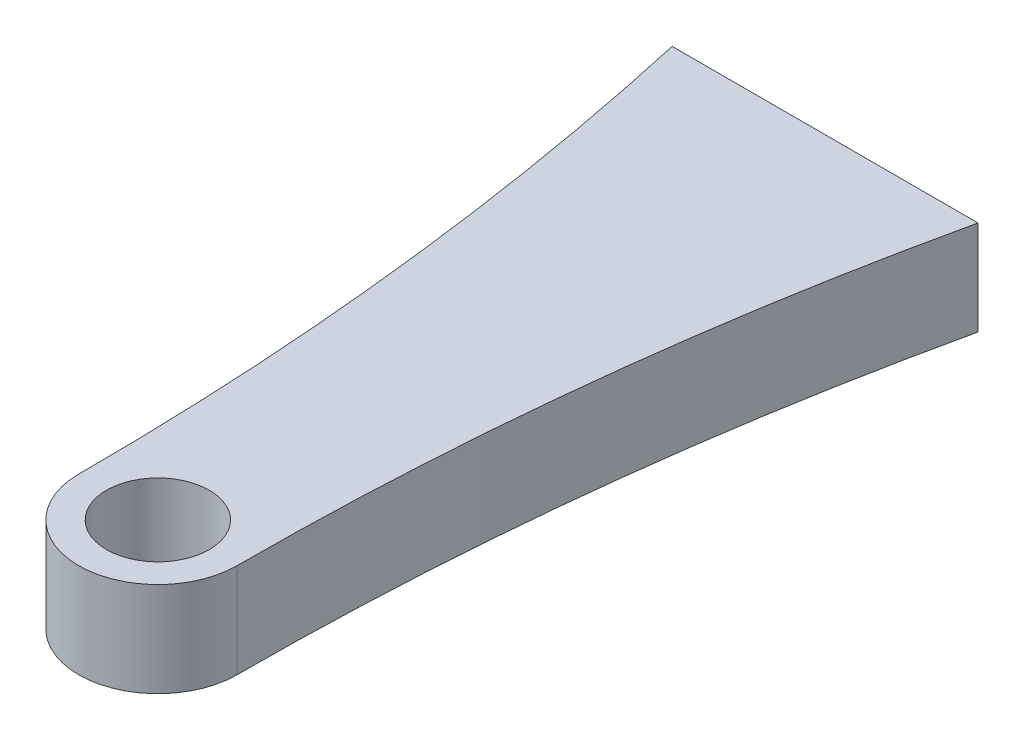
SolidWorks part; units mm, degrees
ref_plane "Front Plane" through (0, 0, 0) normal (0, 0, 1) x (1, 0, 0)
ref_plane "Top Plane" through (0, 0, 0) normal (0, 1, 0) x (1, 0, 0)
ref_plane "Right Plane" through (0, 0, 0) normal (1, 0, 0) x (0, 0, -1)
sketch "Sketch1" plane through (0, 0, 0) normal (0, 1, 0) x (1, 0, 0)
  line L0 (-34.925, 152.4) -> (34.925, 152.4)
  line L1 (0, 0) -> (0, 152.4) construction
  circle A0 centre (0, 0) radius 11.7475
  circle A1 centre (0, 0) radius 152.4 construction
  arc A2 (-18.0975, 0) -> (18.0975, 0) centre (0, 0) ccw
  arc A3 (-34.925, 152.4) -> (-18.0975, 0) centre (-716.6245, 0) cw
  arc A4 (34.925, 152.4) -> (18.0975, 0) centre (716.6245, 0) ccw
  circle A6 centre (0, 0) radius 18.0975 construction
  point P7 (0, 152.4)
  point P14 (18.0975, 0)
  dimension "D1" = 23.495
  dimension "D2" = 152.4
  dimension "D4" = 69.85
  dimension "D3" = 6.35
extrude "Boss-Extrude1" add sketch "Sketch1" along normal mid plane 21.59
sketch "Sketch3" plane through (0, 0, -152.4) normal (0, 0, -1) x (-1, 0, 0)
  line L0 (-1000, 0) -> (49000, 0) construction
  line L1 (0, -15.5111) -> (0, 15.5111) construction
  circle A0 centre (-25.4, 0) radius 3.175
  circle A1 centre (25.4, 0) radius 3.175
  point P6 (0, 0)
  dimension "D1" = 6.35
  dimension "D2" = 25.4
